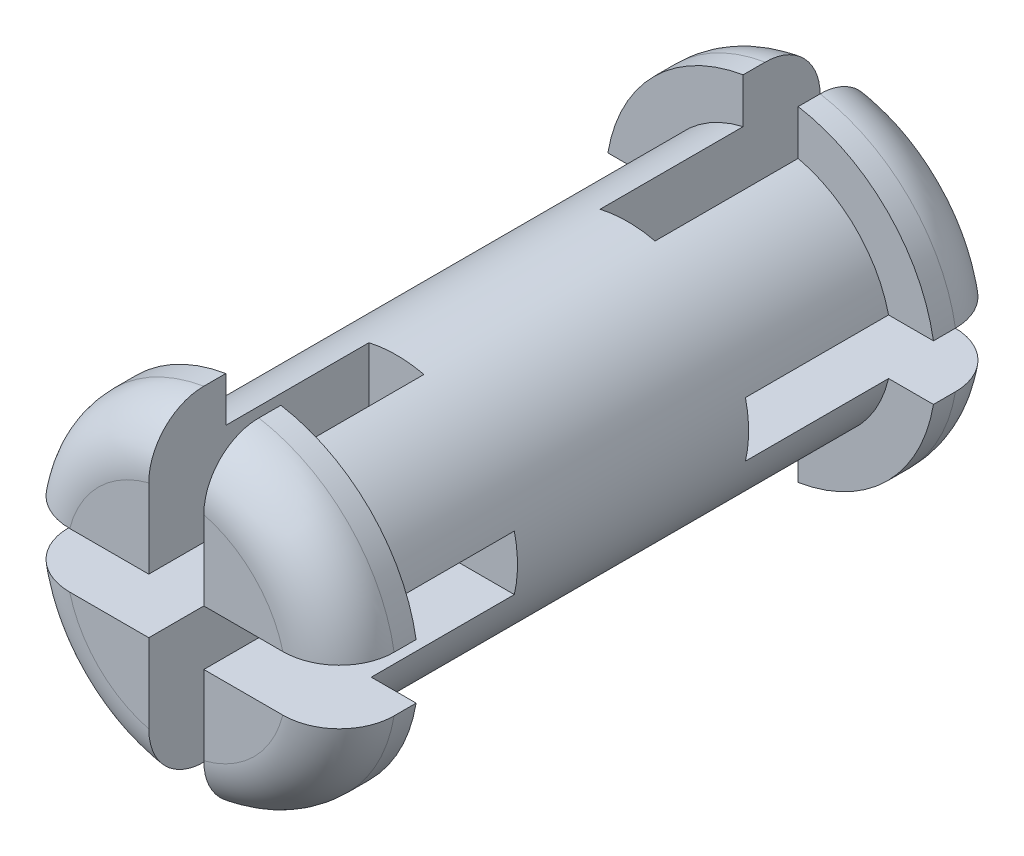
SolidWorks part; units mm, degrees
material "PLA"
ref_plane "Front" through (0, 0, 0) normal (0, 0, 1) x (1, 0, 0)
ref_plane "Top" through (0, 0, 0) normal (0, 1, 0) x (1, 0, 0)
ref_plane "Right" through (0, 0, 0) normal (1, 0, 0) x (0, 0, -1)
sketch "Sketch1" plane through (0, 0, 0) normal (0, 0, 1) x (1, 0, 0)
  circle A0 centre (-0.3912, -94.2158) radius 2.794
  dimension "D1" = 5.588
extrude "Boss-Extrude1" add sketch "Sketch1" along normal offset from surface (7.747 mm away) 1.905
sketch "Sketch2" plane through (0, 0, 7.747) normal (0, 0, 1) x (1, 0, 0)
  line L1 (2.4028, -93.5808) -> (-3.1852, -93.5808)
  line L2 (2.4028, -93.5808) -> (2.4028, -94.8508)
  line L3 (2.4028, -94.8508) -> (-3.1852, -94.8508)
  line L4 (-3.1852, -93.5808) -> (-3.1852, -94.8508)
  line L5 (-1.0262, -91.4218) -> (0.2438, -91.4218)
  line L6 (-1.0262, -91.4218) -> (-1.0262, -97.0098)
  line L7 (-1.0262, -97.0098) -> (0.2438, -97.0098)
  line L8 (0.2438, -91.4218) -> (0.2438, -97.0098)
  circle A0 centre (-0.3912, -94.2158) radius 2.794 construction
  circle M9 centre (-0.3912, -94.2158) radius 2.794
  dimension "D1" = 1.27
  dimension "D2" = 2.159
  dimension "D3" = 2.159
extrude "Cut-Extrude1" cut sketch "Sketch2" against normal blind 5.08 contours L1 L8 L3 M9 | L6 L1 L3 M9 | L8 L6 L1 M9 | L8 L3 L6 M9 | L8 L1 L6 L3
sketch "Sketch3" plane through (0, 0, 7.747) normal (0, 0, 1) x (1, 0, 0)
  line L0 (-1.0262, -96.9367) -> (-1.0262, -94.8508) construction
  line L1 (-1.0262, -94.8508) -> (-3.1121, -94.8508) construction
  line L2 (-3.1121, -93.5808) -> (-1.0262, -93.5808) construction
  line L3 (-1.0262, -93.5808) -> (-1.0262, -91.4949) construction
  line L4 (0.2438, -91.4949) -> (0.2438, -93.5808) construction
  line L5 (0.2438, -93.5808) -> (2.3297, -93.5808) construction
  line L6 (2.3297, -94.8508) -> (0.2438, -94.8508) construction
  line L7 (0.2438, -94.8508) -> (0.2438, -96.9367) construction
  line L8 (-1.0262, -96.9367) -> (-1.0262, -94.8508)
  line L9 (-1.0262, -94.8508) -> (-3.1121, -94.8508)
  line L10 (-3.1121, -93.5808) -> (-1.0262, -93.5808)
  line L11 (-1.0262, -93.5808) -> (-1.0262, -91.4949)
  line L12 (0.2438, -91.4949) -> (0.2438, -93.5808)
  line L13 (0.2438, -93.5808) -> (2.3297, -93.5808)
  line L14 (2.3297, -94.8508) -> (0.2438, -94.8508)
  line L15 (0.2438, -94.8508) -> (0.2438, -96.9367)
  line L16 (3.3655, -93.5808) -> (-4.1479, -93.5808)
  line L17 (3.3655, -94.8508) -> (-4.1479, -94.8508)
  line L18 (0.2438, -97.9725) -> (0.2438, -90.4591)
  line L19 (-1.0262, -97.9725) -> (-1.0262, -90.4591)
  arc A0 (-3.1121, -94.8508) -> (-1.0262, -96.9367) centre (-0.3912, -94.2158) ccw construction
  arc A1 (-1.0262, -91.4949) -> (-3.1121, -93.5808) centre (-0.3912, -94.2158) ccw construction
  arc A2 (2.3297, -93.5808) -> (0.2438, -91.4949) centre (-0.3912, -94.2158) ccw construction
  arc A3 (0.2438, -96.9367) -> (2.3297, -94.8508) centre (-0.3912, -94.2158) ccw construction
  arc A4 (-3.1121, -94.8508) -> (-1.0262, -96.9367) centre (-0.3912, -94.2158) ccw
  arc A5 (-1.0262, -91.4949) -> (-3.1121, -93.5808) centre (-0.3912, -94.2158) ccw
  arc A6 (2.3297, -93.5808) -> (0.2438, -91.4949) centre (-0.3912, -94.2158) ccw
  arc A7 (0.2438, -96.9367) -> (2.3297, -94.8508) centre (-0.3912, -94.2158) ccw
  circle A8 centre (-0.3912, -94.2158) radius 3.81
  point P23 (-2.0692, -93.5808)
  arc M18 (2.3297, -93.5808) -> (0.2438, -91.4949) centre (-0.3912, -94.2158) ccw
  dimension "D1" = 7.62
extrude "Boss-Extrude2" add sketch "Sketch3" against normal blind 1.778 contours L18 A8 L17 A7 | L17 A8 L19 A4 | L19 A8 L16 A5 | L16 A8 L18 M18
fillet "Fillet1" radius 1.27 4 edges at (2.3028, -91.5217, 7.747) (-3.0853, -91.5217, 7.747) (2.3028, -96.9099, 7.747) (-3.0853, -96.9099, 7.747)
mirror "Mirror2" about plane through (-0.3912, -94.2158, 0) normal (0, 0, 1) of bodies 103
